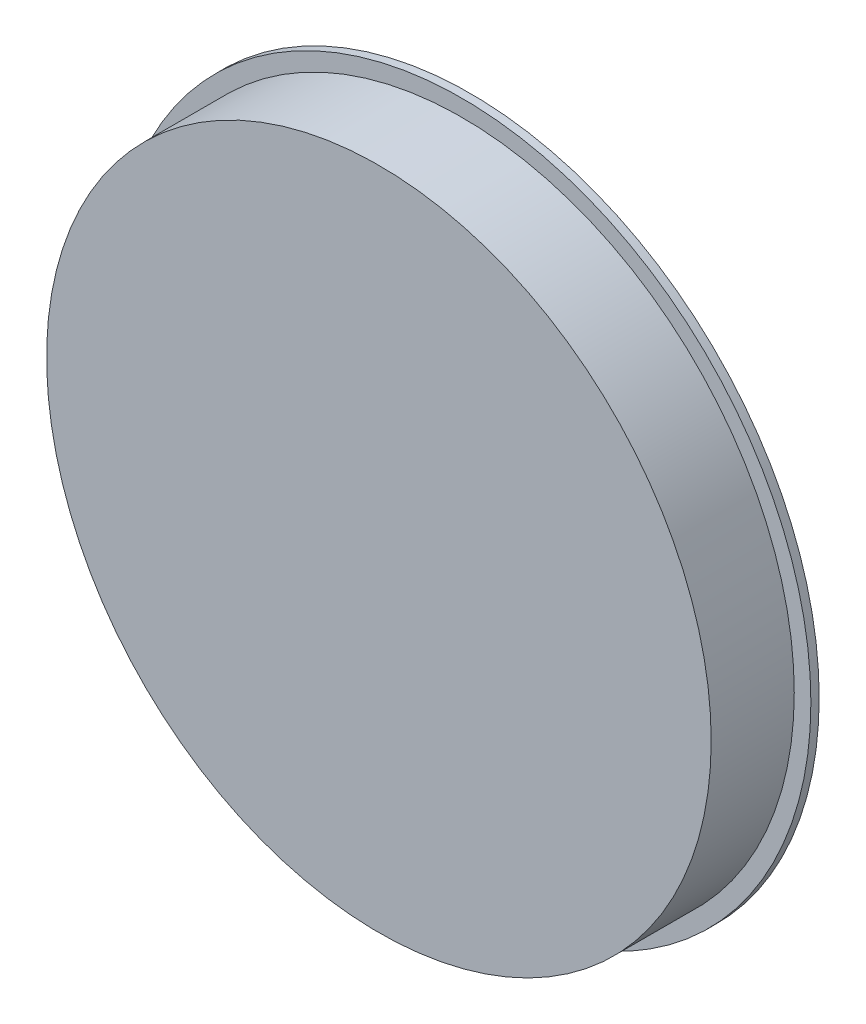
SolidWorks part; units mm, degrees
material "6061-T6 (SS)"
ref_plane "Front Plane" through (0, 0, 0) normal (0, 0, 1) x (1, 0, 0)
ref_plane "Top Plane" through (0, 0, 0) normal (0, 1, 0) x (1, 0, 0)
ref_plane "Right Plane" through (0, 0, 0) normal (1, 0, 0) x (0, 0, -1)
sketch "Sketch1" plane through (0, 0, 0) normal (0, 0, 1) x (1, 0, 0)
  circle A0 centre (0, 0) radius 12.5 construction
  circle A1 centre (0, 0) radius 12.5
extrude "Boss-Extrude1" add sketch "Sketch1" against normal up to surface (3.175 mm away)
sketch "Sketch2" plane through (0, 0, 0) normal (0, 0, 1) x (1, 0, 0)
  circle A0 centre (0, 0) radius 42
extrude "Boss-Extrude2" add sketch "Sketch2" along normal up to vertex (1 mm away)
sketch "Sketch3" plane through (0, 0, 1) normal (0, 0, 1) x (1, 0, 0)
  circle A0 centre (0, 0) radius 40 construction
  circle A1 centre (0, 0) radius 40
extrude "Boss-Extrude3" add sketch "Sketch3" along normal up to vertex (10 mm away)
